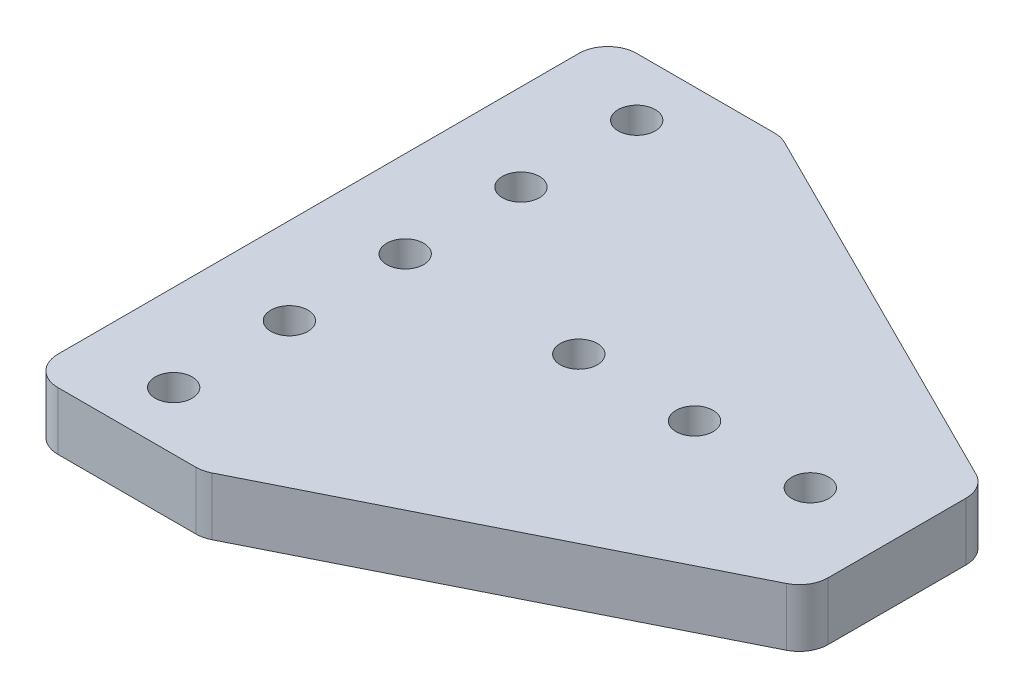
SolidWorks part; units mm, degrees
ref_plane "Front Plane" through (0, 0, 0) normal (0, 0, 1) x (1, 0, 0)
ref_plane "Top Plane" through (0, 0, 0) normal (0, 1, 0) x (1, 0, 0)
ref_plane "Right Plane" through (0, 0, 0) normal (1, 0, 0) x (0, 0, -1)
sketch "Sketch1" plane through (0, 0, 0) normal (0, 1, 0) x (1, 0, 0)
  line L5 (0, 0) -> (0, 127)
  line L6 (0, 127) -> (38.1, 127)
  line L7 (38.1, 127) -> (127, 82.55)
  line L8 (127, 82.55) -> (127, 44.45)
  line L9 (127, 44.45) -> (38.1, 0)
  line L10 (38.1, 0) -> (0, 0)
  line L11 (127, 63.5) -> (0, 63.5) construction
  line L12 (19.05, 0) -> (19.05, 127) construction
  circle A0 centre (19.05, 12.7) radius 4.064
  circle A2 centre (19.05, 38.1) radius 4.064
  circle A3 centre (19.05, 63.5) radius 4.064
  circle A4 centre (19.05, 88.9) radius 4.064
  circle A5 centre (19.05, 114.3) radius 4.064
  circle A6 centre (107.95, 63.5) radius 4.064
  circle A7 centre (82.55, 63.5) radius 4.064
  circle A8 centre (57.15, 63.5) radius 4.064
  dimension "D5" = 8.128
  dimension "D7" = 5
  dimension "D9" = 8.128
  dimension "D1" = 38.1
  dimension "D2" = 127
  dimension "D3" = 38.1
  dimension "D4" = 127
  dimension "D6" = 12.7
  dimension "D8" = 12.7
  dimension "D10" = 19.05
  dimension "D12" = 38.1
  dimension "D13" = 25.4
  dimension "D14" = 25.4
  dimension "D11" = 3
extrude "Boss-Extrude1" add sketch "Sketch1" along normal blind 12.7
fillet "Fillet1" radius 6.35 6 edges at (38.1, 6.35, -127) (0, 6.35, -127) (0, 6.35, 0) (127, 6.35, -82.55) (127, 6.35, -44.45) (38.1, 6.35, 0)
